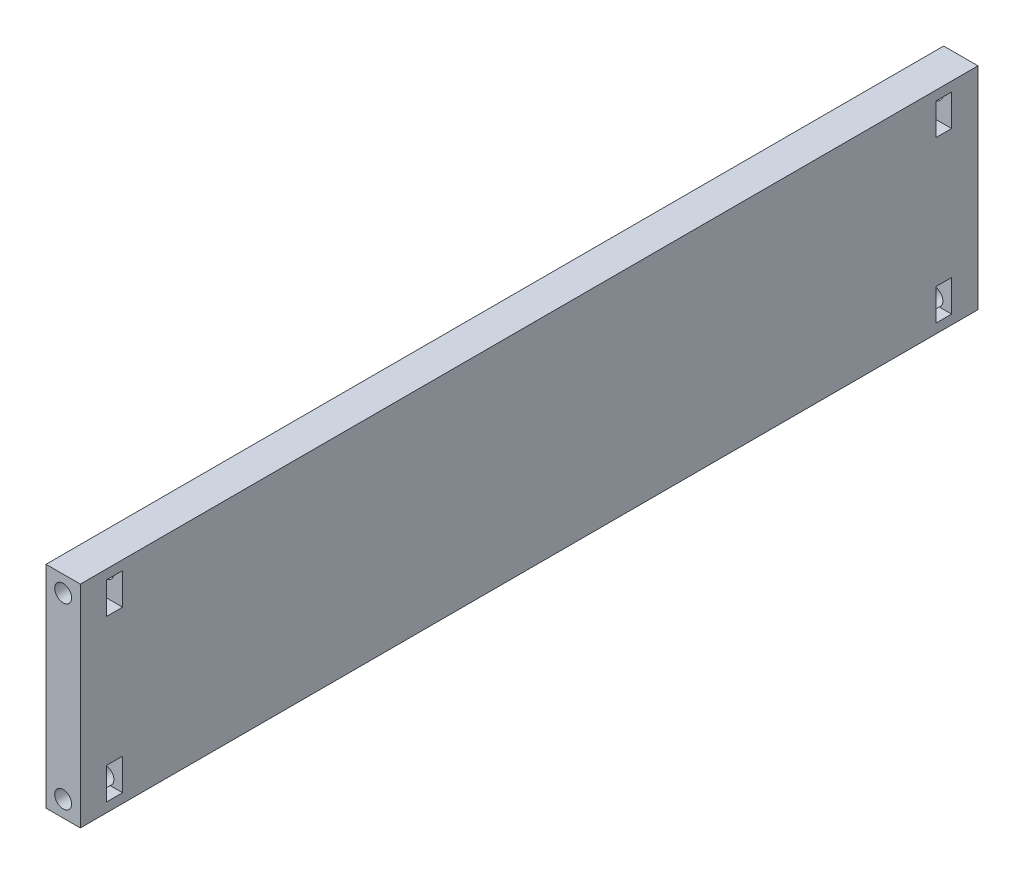
SolidWorks part; units mm, degrees
ref_plane "前视基准面" through (0, 0, 0) normal (0, 0, 1) x (1, 0, 0)
ref_plane "上视基准面" through (0, 0, 0) normal (0, 1, 0) x (1, 0, 0)
ref_plane "右视基准面" through (0, 0, 0) normal (1, 0, 0) x (0, 0, -1)
sketch "草图1" plane through (0, 0, 0) normal (1, 0, 0) x (0, 0, -1)
  line L1 (0, 0) -> (170, 0)
  line L2 (0, 0) -> (0, 40)
  line L3 (0, 40) -> (170, 40)
  line L4 (170, 0) -> (170, 40)
  line L23 (5, 7.7861) -> (8, 7.7861)
  line L24 (8, 1.7861) -> (8, 7.7861)
  line L25 (5, 1.7861) -> (8, 1.7861)
  line L26 (5, 1.7861) -> (5, 7.7861)
  line L34 (5, 38.2139) -> (5, 32.2139)
  line L35 (5, 38.2139) -> (8, 38.2139)
  line L36 (8, 38.2139) -> (8, 32.2139)
  line L37 (5, 32.2139) -> (8, 32.2139)
  line L54 (165, 1.7861) -> (165, 7.7861)
  line L55 (165, 1.7861) -> (162, 1.7861)
  line L56 (162, 1.7861) -> (162, 7.7861)
  line L57 (165, 7.7861) -> (162, 7.7861)
  line L58 (165, 38.2139) -> (162, 38.2139)
  line L59 (162, 38.2139) -> (162, 32.2139)
  line L60 (165, 32.2139) -> (162, 32.2139)
  line L61 (165, 38.2139) -> (165, 32.2139)
  dimension "D1" = 170
  dimension "D2" = 40
extrude "凸台-拉伸2" add sketch "草图1" along normal blind 6.5
sketch "草图4" plane through (0, 0, 0) normal (0, 0, 1) x (1, 0, 0)
  circle A0 centre (3.25, 36.9) radius 1.6
  circle A1 centre (3.25, 3.1) radius 1.6
extrude "切除-拉伸1" cut sketch "草图4" against normal blind 25
sketch "草图5" plane through (0, 0, -170) normal (0, 0, -1) x (-1, 0, 0)
  circle A2 centre (-3.25, 36.9) radius 1.6
  circle A3 centre (-3.25, 3.1) radius 1.6
extrude "切除-拉伸2" cut sketch "草图5" against normal blind 25
sketch "草图6" plane through (6.5, 0, 0) normal (1, 0, 0) x (0, 0, -1)
  line L0 (85, 0) -> (85, 40)
  line L2 (0, 0) -> (170, 0) construction
  line L3 (170, 40) -> (0, 40) construction
sketch "草图7" plane through (0, 40, 0) normal (0, 1, 0) x (1, 0, 0)
  line L0 (0, 85) -> (6.5, 85)
  line L3 (0, 170) -> (0, 0) construction
  line L4 (6.5, 170) -> (6.5, 0) construction
